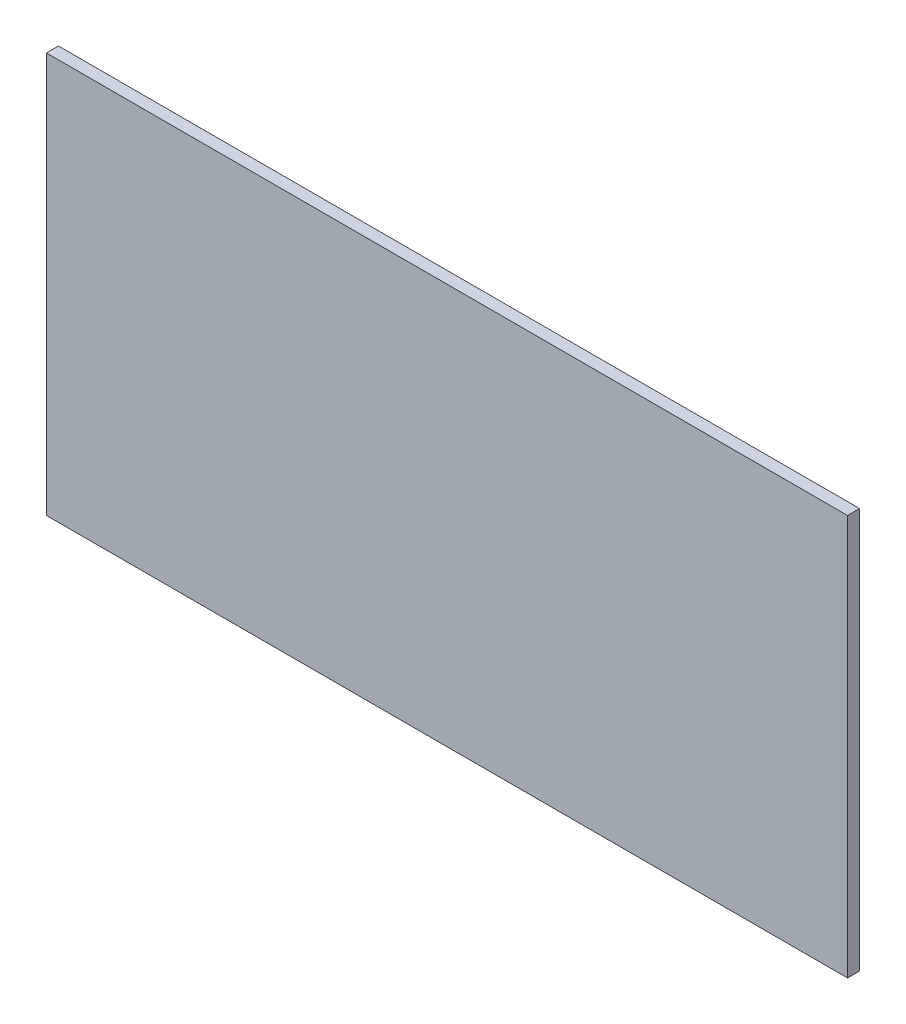
SolidWorks part; units mm, degrees
material "6063-T1"
ref_plane "Front Plane" through (0, 0, 0) normal (0, 0, 1) x (1, 0, 0)
ref_plane "Top Plane" through (0, 0, 0) normal (0, 1, 0) x (1, 0, 0)
ref_plane "Right Plane" through (0, 0, 0) normal (1, 0, 0) x (0, 0, -1)
sketch "Sketch1" plane through (0, 0, 0) normal (0, 0, 1) x (1, 0, 0)
  line L1 (0, 0) -> (-100, 0)
  line L2 (0, 0) -> (0, -50)
  line L3 (0, -50) -> (-100, -50)
  line L4 (-100, 0) -> (-100, -50)
  dimension "D1" = 100
  dimension "D2" = 50
extrude "Boss-Extrude1" add sketch "Sketch1" along normal blind 1.5
